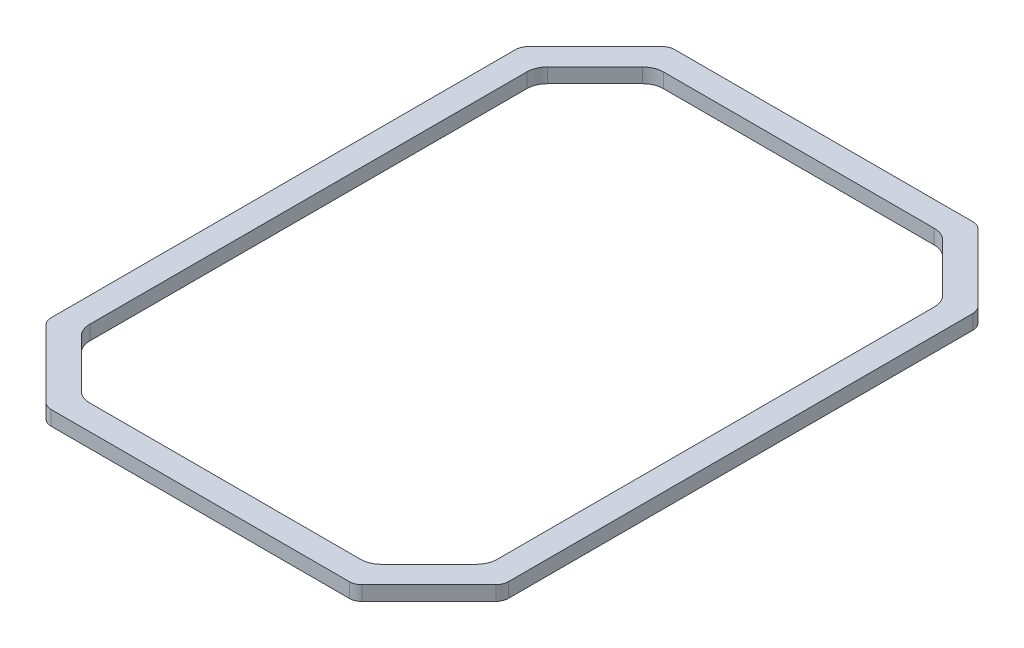
SolidWorks part; units mm, degrees
ref_plane "Front Plane" through (0, 0, 0) normal (0, 0, 1) x (1, 0, 0)
ref_plane "Top Plane" through (0, 0, 0) normal (0, 1, 0) x (1, 0, 0)
ref_plane "Right Plane" through (0, 0, 0) normal (1, 0, 0) x (0, 0, -1)
sketch "Sketch1" plane through (-905.7837, 0, -1752.4807) normal (0, 1, 0) x (1, 0, 0)
  line L0 (5.8681, -1.2898) -> (-2.1929, -9.3508)
  line L1 (-2.6323, -10.4115) -> (-2.6323, -66.2894)
  line L2 (-2.1929, -67.3501) -> (5.8681, -75.4111)
  line L3 (6.9288, -75.8505) -> (42.8067, -75.8505)
  line L4 (43.8674, -75.4111) -> (51.9284, -67.3501)
  line L5 (52.3677, -66.2894) -> (52.3677, -10.4115)
  line L6 (51.9284, -9.3508) -> (43.8674, -1.2898)
  line L7 (42.8067, -0.8505) -> (6.9288, -0.8505)
  line L8 (52.282, -8.9973) -> (44.2209, -0.9362)
  line L9 (42.8067, -0.3505) -> (6.9288, -0.3505)
  line L10 (5.5145, -0.9362) -> (-2.5465, -8.9973)
  line L11 (-3.1323, -10.4115) -> (-3.1323, -66.2894)
  line L12 (-2.5465, -67.7036) -> (5.5145, -75.7647)
  line L13 (6.9288, -76.3505) -> (42.8067, -76.3505)
  line L14 (44.2209, -75.7647) -> (52.282, -67.7036)
  line L15 (52.8677, -66.2894) -> (52.8677, -10.4115)
  line L16 (52.282, -8.9973) -> (44.2209, -0.9362) construction
  line L17 (42.8067, -0.3505) -> (6.9288, -0.3505) construction
  line L18 (5.5145, -0.9362) -> (-2.5465, -8.9973) construction
  line L19 (-3.1323, -10.4115) -> (-3.1323, -66.2894) construction
  line L20 (-2.5465, -67.7036) -> (5.5145, -75.7647) construction
  line L21 (6.9288, -76.3505) -> (42.8067, -76.3505) construction
  line L22 (44.2209, -75.7647) -> (52.282, -67.7036) construction
  line L23 (52.8677, -66.2894) -> (52.8677, -10.4115) construction
  line L24 (1.4535, -66.0468) -> (7.1714, -71.7647)
  line L25 (0.8677, -12.0683) -> (0.8677, -64.6326)
  line L26 (7.1714, -4.9362) -> (1.4535, -10.6541)
  line L27 (41.1499, -4.3505) -> (8.5856, -4.3505)
  line L28 (48.282, -10.6541) -> (42.5641, -4.9362)
  line L29 (48.8677, -64.6326) -> (48.8677, -12.0683)
  line L30 (42.5641, -71.7647) -> (48.282, -66.0468)
  line L31 (8.5856, -72.3505) -> (41.1499, -72.3505)
  line L32 (1.4535, -66.0468) -> (7.1714, -71.7647) construction
  line L33 (0.8677, -12.0683) -> (0.8677, -64.6326) construction
  line L34 (7.1714, -4.9362) -> (1.4535, -10.6541) construction
  line L35 (41.1499, -4.3505) -> (8.5856, -4.3505) construction
  line L36 (48.282, -10.6541) -> (42.5641, -4.9362) construction
  line L37 (48.8677, -64.6326) -> (48.8677, -12.0683) construction
  line L38 (42.5641, -71.7647) -> (48.282, -66.0468) construction
  line L39 (8.5856, -72.3505) -> (41.1499, -72.3505) construction
  line L40 (6.8178, -4.5827) -> (1.1, -10.3006)
  line L41 (0.3677, -12.0683) -> (0.3677, -64.6326)
  line L42 (1.1, -66.4003) -> (6.8178, -72.1182)
  line L43 (8.5856, -72.8505) -> (41.1499, -72.8505)
  line L44 (42.9176, -72.1182) -> (48.6355, -66.4003)
  line L45 (49.3677, -64.6326) -> (49.3677, -12.0683)
  line L46 (48.6355, -10.3006) -> (42.9176, -4.5827)
  line L47 (41.1499, -3.8505) -> (8.5856, -3.8505)
  arc A0 (-2.1929, -9.3508) -> (-2.6323, -10.4115) centre (-1.1323, -10.4115) ccw
  arc A1 (-2.6323, -66.2894) -> (-2.1929, -67.3501) centre (-1.1323, -66.2894) ccw
  arc A2 (5.8681, -75.4111) -> (6.9288, -75.8505) centre (6.9288, -74.3505) ccw
  arc A3 (42.8067, -75.8505) -> (43.8674, -75.4111) centre (42.8067, -74.3505) ccw
  arc A4 (51.9284, -67.3501) -> (52.3677, -66.2894) centre (50.8677, -66.2894) ccw
  arc A5 (52.3677, -10.4115) -> (51.9284, -9.3508) centre (50.8677, -10.4115) ccw
  arc A6 (43.8674, -1.2898) -> (42.8067, -0.8505) centre (42.8067, -2.3505) ccw
  arc A7 (6.9288, -0.8505) -> (5.8681, -1.2898) centre (6.9288, -2.3505) ccw
  arc A8 (44.2209, -0.9362) -> (42.8067, -0.3505) centre (42.8067, -2.3505) ccw
  arc A9 (6.9288, -0.3505) -> (5.5145, -0.9362) centre (6.9288, -2.3505) ccw
  arc A10 (-2.5465, -8.9973) -> (-3.1323, -10.4115) centre (-1.1323, -10.4115) ccw
  arc A11 (-3.1323, -66.2894) -> (-2.5465, -67.7036) centre (-1.1323, -66.2894) ccw
  arc A12 (5.5145, -75.7647) -> (6.9288, -76.3505) centre (6.9288, -74.3505) ccw
  arc A13 (42.8067, -76.3505) -> (44.2209, -75.7647) centre (42.8067, -74.3505) ccw
  arc A14 (52.282, -67.7036) -> (52.8677, -66.2894) centre (50.8677, -66.2894) ccw
  arc A15 (52.8677, -10.4115) -> (52.282, -8.9973) centre (50.8677, -10.4115) ccw
  arc A16 (44.2209, -0.9362) -> (42.8067, -0.3505) centre (42.8067, -2.3505) ccw construction
  arc A17 (6.9288, -0.3505) -> (5.5145, -0.9362) centre (6.9288, -2.3505) ccw construction
  arc A18 (-2.5465, -8.9973) -> (-3.1323, -10.4115) centre (-1.1323, -10.4115) ccw construction
  arc A19 (-3.1323, -66.2894) -> (-2.5465, -67.7036) centre (-1.1323, -66.2894) ccw construction
  arc A20 (5.5145, -75.7647) -> (6.9288, -76.3505) centre (6.9288, -74.3505) ccw construction
  arc A21 (42.8067, -76.3505) -> (44.2209, -75.7647) centre (42.8067, -74.3505) ccw construction
  arc A22 (52.282, -67.7036) -> (52.8677, -66.2894) centre (50.8677, -66.2894) ccw construction
  arc A23 (52.8677, -10.4115) -> (52.282, -8.9973) centre (50.8677, -10.4115) ccw construction
  arc A24 (0.8677, -64.6326) -> (1.4535, -66.0468) centre (2.8677, -64.6326) ccw
  arc A25 (1.4535, -10.6541) -> (0.8677, -12.0683) centre (2.8677, -12.0683) ccw
  arc A26 (8.5856, -4.3505) -> (7.1714, -4.9362) centre (8.5856, -6.3505) ccw
  arc A27 (42.5641, -4.9362) -> (41.1499, -4.3505) centre (41.1499, -6.3505) ccw
  arc A28 (48.8677, -12.0683) -> (48.282, -10.6541) centre (46.8677, -12.0683) ccw
  arc A29 (48.282, -66.0468) -> (48.8677, -64.6326) centre (46.8677, -64.6326) ccw
  arc A30 (41.1499, -72.3505) -> (42.5641, -71.7647) centre (41.1499, -70.3505) ccw
  arc A31 (7.1714, -71.7647) -> (8.5856, -72.3505) centre (8.5856, -70.3505) ccw
  arc A32 (0.8677, -64.6326) -> (1.4535, -66.0468) centre (2.8677, -64.6326) ccw construction
  arc A33 (1.4535, -10.6541) -> (0.8677, -12.0683) centre (2.8677, -12.0683) ccw construction
  arc A34 (8.5856, -4.3505) -> (7.1714, -4.9362) centre (8.5856, -6.3505) ccw construction
  arc A35 (42.5641, -4.9362) -> (41.1499, -4.3505) centre (41.1499, -6.3505) ccw construction
  arc A36 (48.8677, -12.0683) -> (48.282, -10.6541) centre (46.8677, -12.0683) ccw construction
  arc A37 (48.282, -66.0468) -> (48.8677, -64.6326) centre (46.8677, -64.6326) ccw construction
  arc A38 (41.1499, -72.3505) -> (42.5641, -71.7647) centre (41.1499, -70.3505) ccw construction
  arc A39 (7.1714, -71.7647) -> (8.5856, -72.3505) centre (8.5856, -70.3505) ccw construction
  arc A40 (1.1, -10.3006) -> (0.3677, -12.0683) centre (2.8677, -12.0683) ccw
  arc A41 (0.3677, -64.6326) -> (1.1, -66.4003) centre (2.8677, -64.6326) ccw
  arc A42 (6.8178, -72.1182) -> (8.5856, -72.8505) centre (8.5856, -70.3505) ccw
  arc A43 (41.1499, -72.8505) -> (42.9176, -72.1182) centre (41.1499, -70.3505) ccw
  arc A44 (48.6355, -66.4003) -> (49.3677, -64.6326) centre (46.8677, -64.6326) ccw
  arc A45 (49.3677, -12.0683) -> (48.6355, -10.3006) centre (46.8677, -12.0683) ccw
  arc A46 (42.9176, -4.5827) -> (41.1499, -3.8505) centre (41.1499, -6.3505) ccw
  arc A47 (8.5856, -3.8505) -> (6.8178, -4.5827) centre (8.5856, -6.3505) ccw
  dimension "D1" = 0
  dimension "D2" = 0
  dimension "D3" = 0.5
  dimension "D4" = 0.5
extrude "Boss-Extrude1" add sketch "Sketch1" along normal blind 1.75
